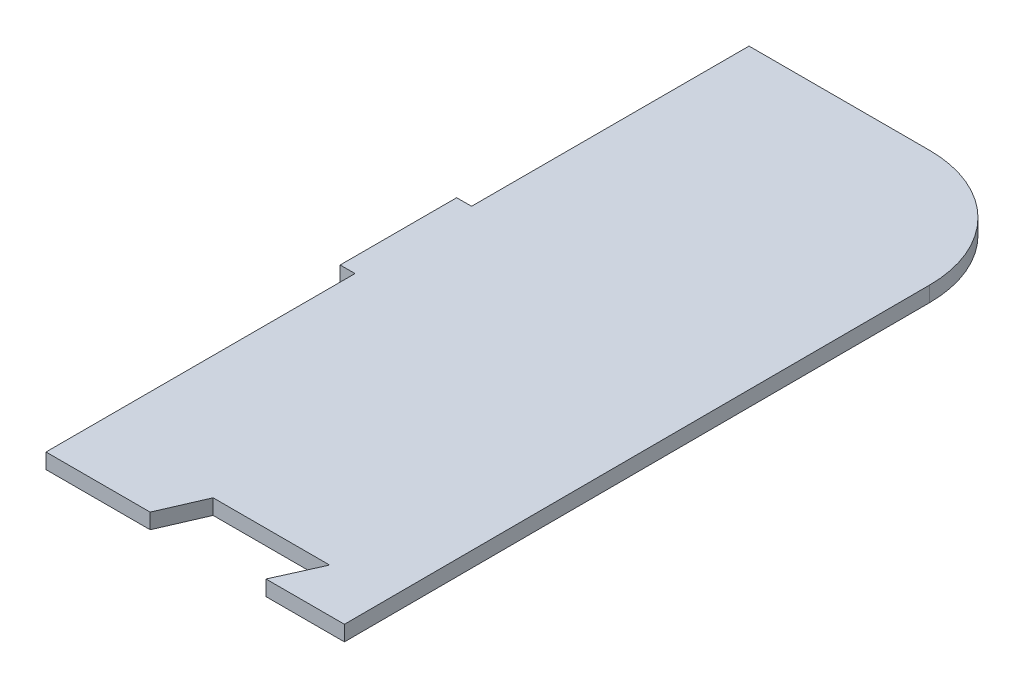
SolidWorks part; units mm, degrees
ref_plane "Front Plane" through (0, 0, 0) normal (0, 0, 1) x (1, 0, 0)
ref_plane "Top Plane" through (0, 0, 0) normal (0, 1, 0) x (1, 0, 0)
ref_plane "Right Plane" through (0, 0, 0) normal (1, 0, 0) x (0, 0, -1)
sketch "Sketch1" plane through (0, 0, 0) normal (0, 0, 1) x (1, 0, 0)
  line L1 (358.1218, 754.38) -> (137.9613, 754.38)
  line L2 (358.1218, 754.38) -> (562.8036, 754.38)
  line L3 (562.8036, 754.38) -> (562.8036, 744.38)
  line L4 (562.8036, 744.38) -> (137.9613, 744.38)
  line L5 (137.9613, 744.38) -> (137.9613, 754.38)
  dimension "D1" = 10
extrude "Boss-Extrude1" add sketch "Sketch1" along normal up to surface (459.74 mm away)
sketch "Sketch3" plane through (0, 744.38, 0) normal (0, -1, 0) x (1, 0, 0)
  line L0 (255.63, 0) -> (255.63, 459.74)
  line L1 (137.9613, 0) -> (562.8036, 0) construction
  line L2 (137.9613, 459.74) -> (562.8036, 459.74) construction
  line L3 (255.63, 459.74) -> (137.9613, 459.74)
  line L4 (137.9613, 459.74) -> (137.9613, 0)
  line L5 (137.9613, 0) -> (255.63, 0)
extrude "Cut-Extrude1" cut sketch "Sketch3" against normal blind 10
sketch "Sketch4" plane through (0, 754.38, 0) normal (0, 1, 0) x (1, 0, 0)
  line L0 (265.3552, -459.74) -> (265.3552, -257.6601)
  line L1 (562.8036, -459.74) -> (255.63, -459.74) construction
  line L2 (562.8036, 0) -> (255.63, 0) construction
  line L3 (265.3552, -459.74) -> (255.63, -459.74)
  line L4 (255.63, -459.74) -> (255.63, -257.6601)
  line L5 (229.0383, -257.6601) -> (265.3552, -257.6601) construction
  line L6 (229.0383, -181.4601) -> (265.3552, -181.4601) construction
  line L7 (265.3552, -459.74) -> (255.63, -459.74)
  line L8 (265.3552, -257.6601) -> (255.63, -257.6601)
  line L9 (265.3552, -181.4601) -> (255.63, -181.4601)
  line L10 (255.63, -181.4601) -> (255.63, 0)
  line L11 (265.3552, -181.4601) -> (265.3552, 0)
  line L12 (333.4642, -459.74) -> (369.7619, -561.8393)
  line L13 (333.4642, -459.74) -> (345.9305, -431.0401)
  line L14 (345.9305, -431.0401) -> (422.1305, -431.0401)
  line L15 (422.1305, -431.0401) -> (409.2168, -459.74)
  line L16 (409.2168, -459.74) -> (460.5019, -459.74)
  line L17 (460.5019, -459.74) -> (459.7218, -76.2)
  line L18 (369.7619, -561.8393) -> (604.2472, -525.6685)
  line L19 (604.2472, -525.6685) -> (681.4814, 161.1092)
  line L20 (681.4814, 161.1092) -> (358.7401, 101.8465)
  line L21 (358.7401, 101.8465) -> (383.5218, 0)
  line L23 (265.3552, 0) -> (255.63, 0)
  line L24 (255.63, -181.4601) -> (255.63, 0)
  arc A1 (459.7218, -76.2) -> (383.5218, 0) centre (383.5218, -76.2) ccw construction
  arc A2 (459.7218, -76.2) -> (383.5218, 0) centre (383.5218, -76.2) ccw
  line M2 (562.8036, 0) -> (255.63, 0)
  line M3 (255.63, 0) -> (255.63, -459.74)
  line M4 (255.63, -459.74) -> (562.8036, -459.74)
  line M5 (562.8036, -459.74) -> (562.8036, 0)
extrude "Cut-Extrude3" cut sketch "Sketch4" against normal blind 63 contours L0 L8 M3 M4 | L9 L11 M2 M3 | L20 L21 L12 L18 L19 M2 M5 M4
